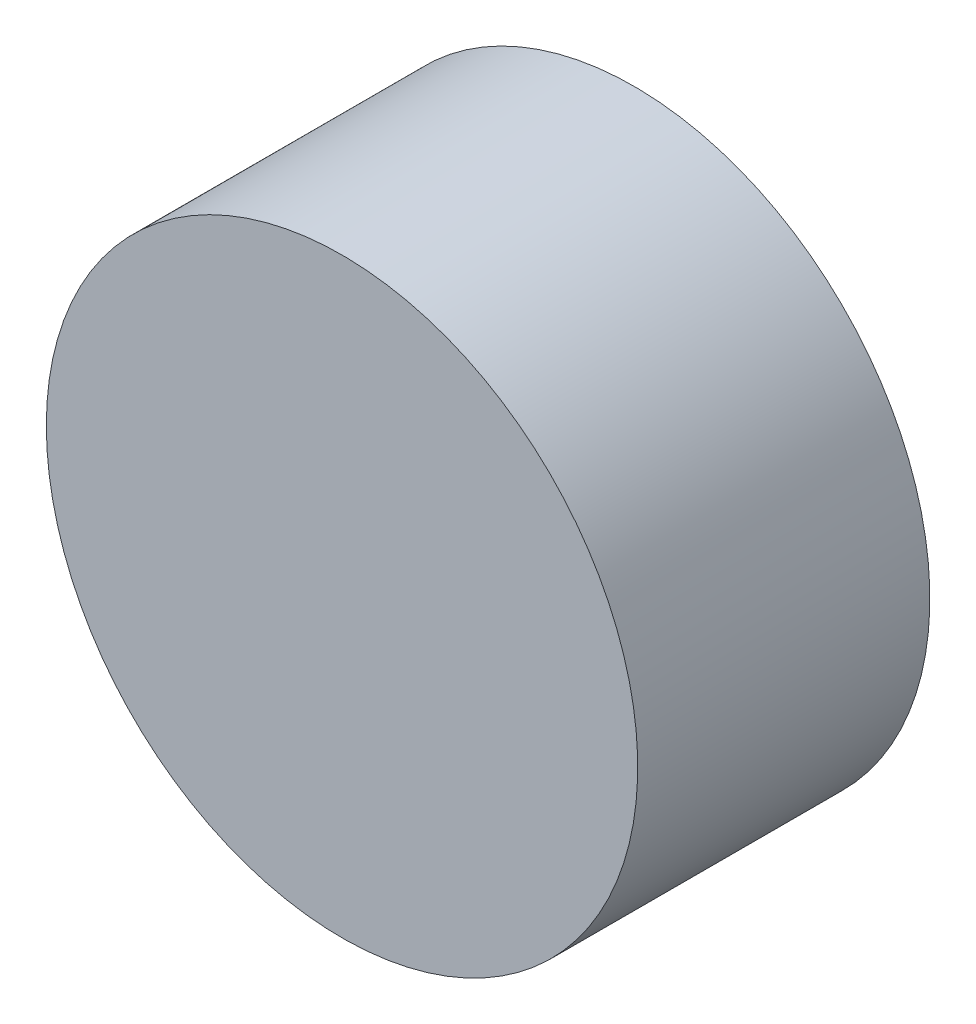
SolidWorks part; units mm, degrees
ref_plane "Front Plane" through (0, 0, 0) normal (0, 0, 1) x (1, 0, 0)
ref_plane "Top Plane" through (0, 0, 0) normal (0, 1, 0) x (1, 0, 0)
ref_plane "Right Plane" through (0, 0, 0) normal (1, 0, 0) x (0, 0, -1)
ref_plane "Plane1" through (0, 0, 0) normal (0, -1, 0) x (1, 0, 0)
sketch "Sketch1" plane through (0, 0, 0) normal (0, -1, 0) x (1, 0, 0)
  line L0 (10.1235, 10) -> (0, 10)
  line L1 (0, 10) -> (0, 0)
  line L2 (0, 0) -> (10.1235, 0)
  line L3 (10.1235, 0) -> (10.1235, 10)
  line L4 (0, 10) -> (0, 0) construction
revolve "Revolve1" add sketch "Sketch1" angle 360 about L4
